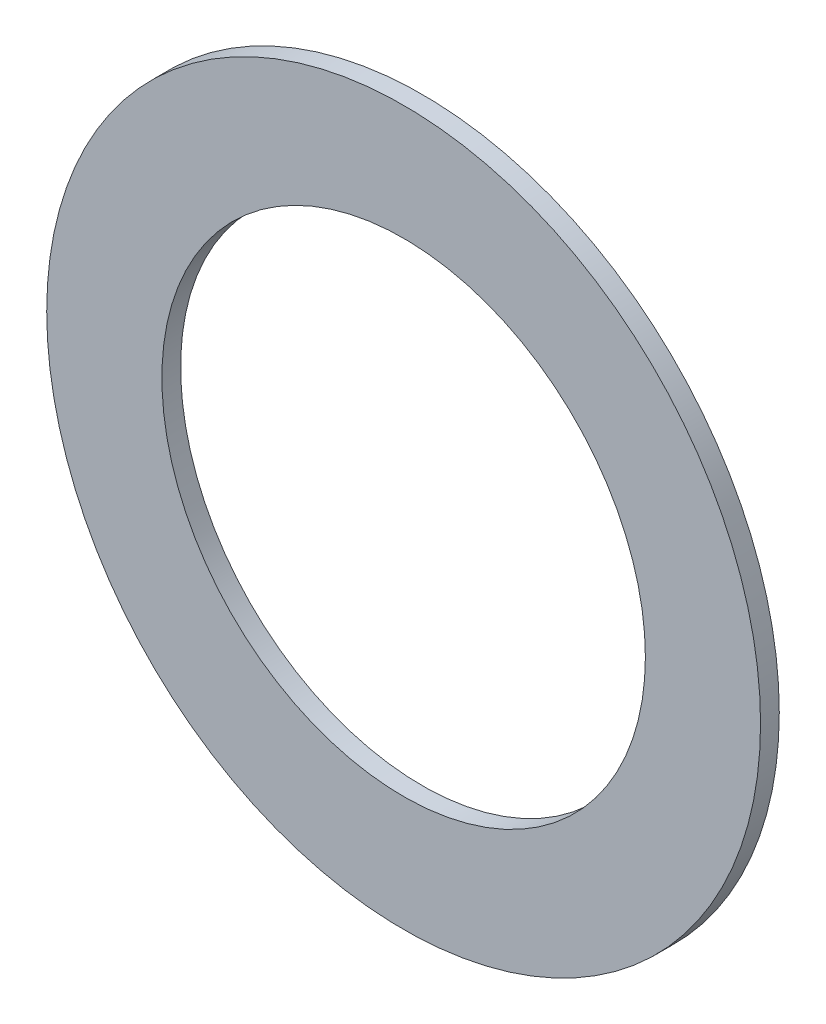
SolidWorks part; units mm, degrees
ref_plane "Front Plane" through (0, 0, 0) normal (0, 0, 1) x (1, 0, 0)
ref_plane "Top Plane" through (0, 0, 0) normal (0, 1, 0) x (1, 0, 0)
ref_plane "Right Plane" through (0, 0, 0) normal (1, 0, 0) x (0, 0, -1)
sketch "Sketch1" plane through (0, 0, 0) normal (0, 0, 1) x (1, 0, 0)
  circle A0 centre (0, 0) radius 76.2
  circle A1 centre (0, 0) radius 51.6125
  dimension "D1" = 152.4
  dimension "D2" = 103.225
extrude "Boss-Extrude1" add sketch "Sketch1" along normal blind 4 contours A0 A1
